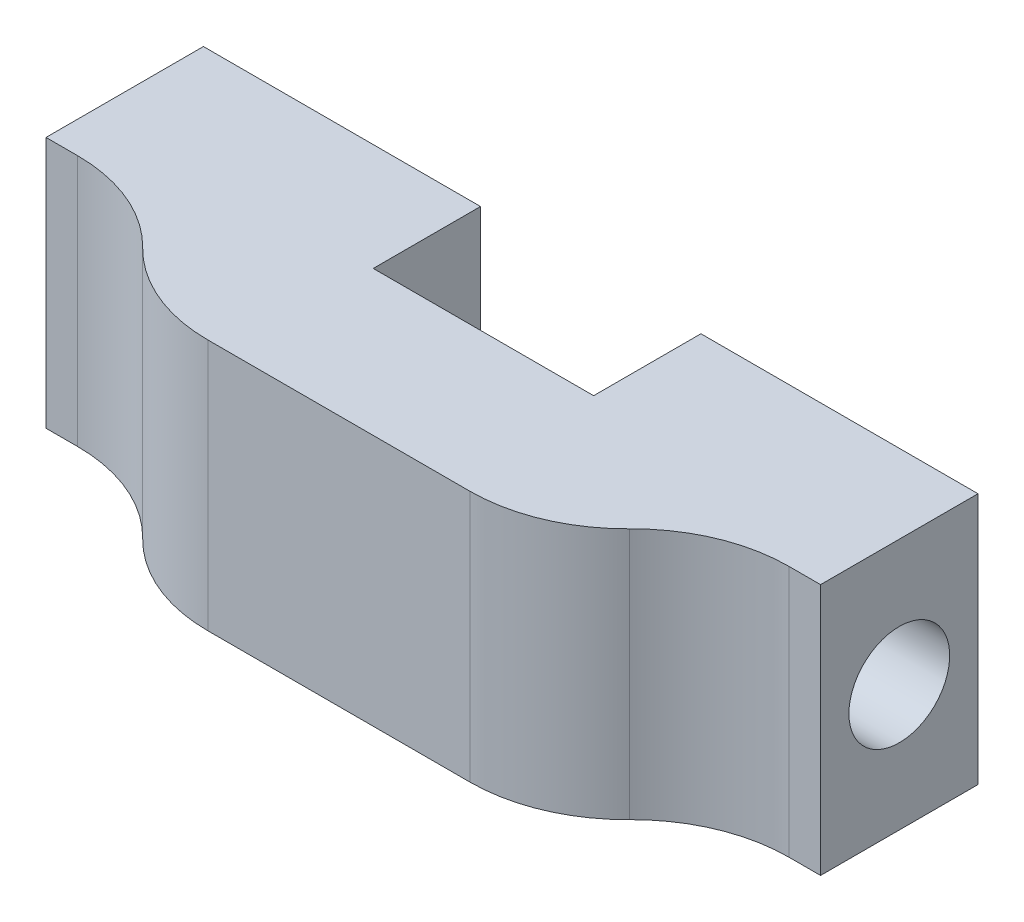
SolidWorks part; units mm, degrees
material "5052-H32"
ref_plane "Front Plane" through (0, 0, 0) normal (0, 0, 1) x (1, 0, 0)
ref_plane "Top Plane" through (0, 0, 0) normal (0, 1, 0) x (1, 0, 0)
ref_plane "Right Plane" through (0, 0, 0) normal (1, 0, 0) x (0, 0, -1)
sketch "Sketch2" plane through (0, 0, 0) normal (0, 1, 0) x (1, 0, 0)
  line L17 (-4.1586, -8) -> (4.1586, -8)
  line L23 (11.3, 0) -> (3.5, 0)
  line L24 (3.5, 0) -> (3.5, -3.4072)
  line L25 (3.5, -3.4072) -> (-3.5, -3.4072)
  line L26 (-3.5, -3.4072) -> (-3.5, 0)
  line L27 (-3.5, 0) -> (-11.3, 0)
  line L28 (-11.3, -5) -> (-12.3, -5)
  line L29 (-12.3, -5) -> (-12.3, 0)
  line L30 (-12.3, 0) -> (-11.3, 0)
  line L31 (11.3, -5) -> (12.3, -5)
  line L32 (12.3, -5) -> (12.3, 0)
  line L33 (12.3, 0) -> (11.3, 0)
  arc A8 (-11.3, -5) -> (-7.7293, -6.5) centre (-11.3, -10) cw
  arc A10 (-7.7293, -6.5) -> (-11.3, -5) centre (-11.3, -10) ccw construction
  arc A12 (-7.7293, -6.5) -> (-4.1586, -8) centre (-4.1586, -3) ccw
  arc A14 (-7.7293, -6.5) -> (-4.1586, -8) centre (-4.1586, -3) ccw construction
  arc A16 (4.1586, -8) -> (7.7293, -6.5) centre (4.1586, -3) ccw
  arc A17 (4.1586, -8) -> (7.7293, -6.5) centre (4.1586, -3) ccw construction
  arc A18 (7.7293, -6.5) -> (11.3, -5) centre (11.3, -10) cw
  arc A19 (11.3, -5) -> (7.7293, -6.5) centre (11.3, -10) ccw construction
extrude "Boss-Extrude1" add sketch "Sketch2" along normal up to vertex (4 mm away) from vertex at -4
hole_wizard "M3 Clearance Hole1" positions "Sketch3" profile "Sketch5" hole size "M3" standard "ISO"
sketch "Sketch3" plane through (-12.3, 0, 0) normal (-1, 0, 0) x (0, 0, 1)
  point P0 (2.5, 0)
  point P4 (0, 0)
sketch "Sketch5" plane through (-12.3, 0, 2.5) normal (0, 1, 0) x (0, 0, 1)
  line L0 (0, 0) -> (0, 8.8)
  line L1 (0, 8.8) -> (1.6, 8.8)
  line L2 (1.6, 8.8) -> (1.6, 0)
  line L5 (1.6, 0) -> (0, 0)
  line L11 (0, -6.35) -> (0, 107.95) construction
  dimension "Thru Hole Dia." = 3.2
  dimension "Thru Hole Depth" = 8.8
mirror "Mirror1" about plane through (0, 0, 0) normal (1, 0, 0) of "M3 Clearance Hole1"
